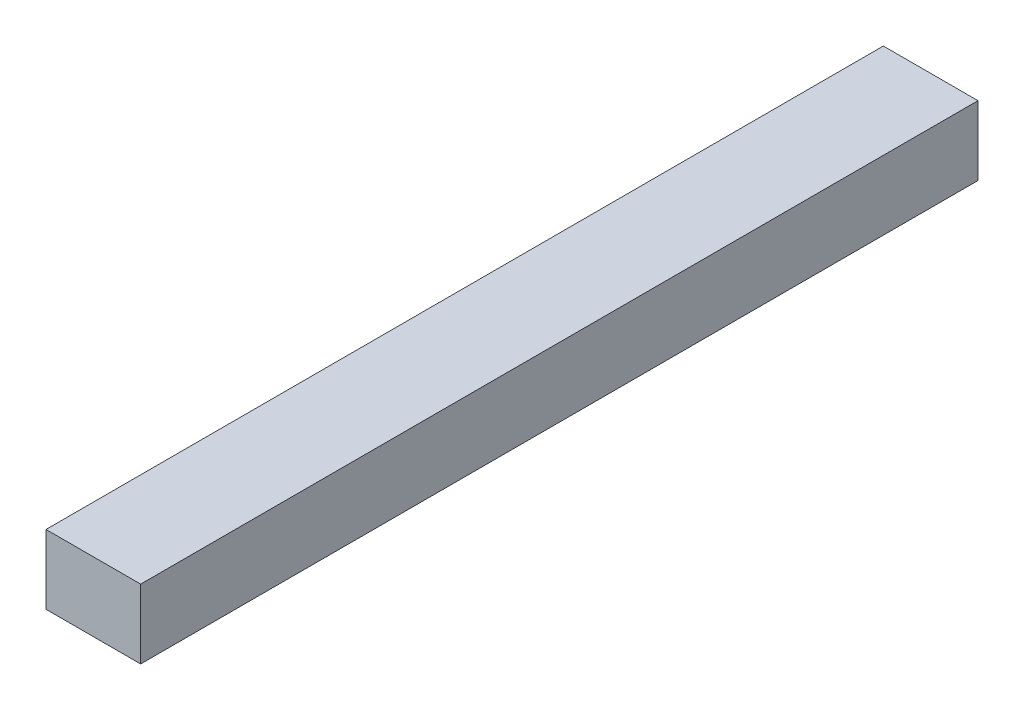
SolidWorks part; units mm, degrees
ref_plane "Front Plane" through (0, 0, 0) normal (0, 0, 1) x (1, 0, 0)
ref_plane "Top Plane" through (0, 0, 0) normal (0, 1, 0) x (1, 0, 0)
ref_plane "Right Plane" through (0, 0, 0) normal (1, 0, 0) x (0, 0, -1)
sketch "Sketch1" plane through (0, 0, 0) normal (0, 0, 1) x (1, 0, 0)
  line L1 (-6.5, 4.75) -> (6.5, 4.75)
  line L2 (-6.5, 4.75) -> (-6.5, -4.75)
  line L3 (-6.5, -4.75) -> (6.5, -4.75)
  line L4 (6.5, 4.75) -> (6.5, -4.75)
  line L5 (-6.5, 4.75) -> (6.5, -4.75) construction
  line L6 (-6.5, -4.75) -> (6.5, 4.75) construction
  point P0 (0, 0)
  dimension "D1" = 9.5
  dimension "D2" = 13
extrude "Boss-Extrude1" add sketch "Sketch1" along normal mid plane 115
